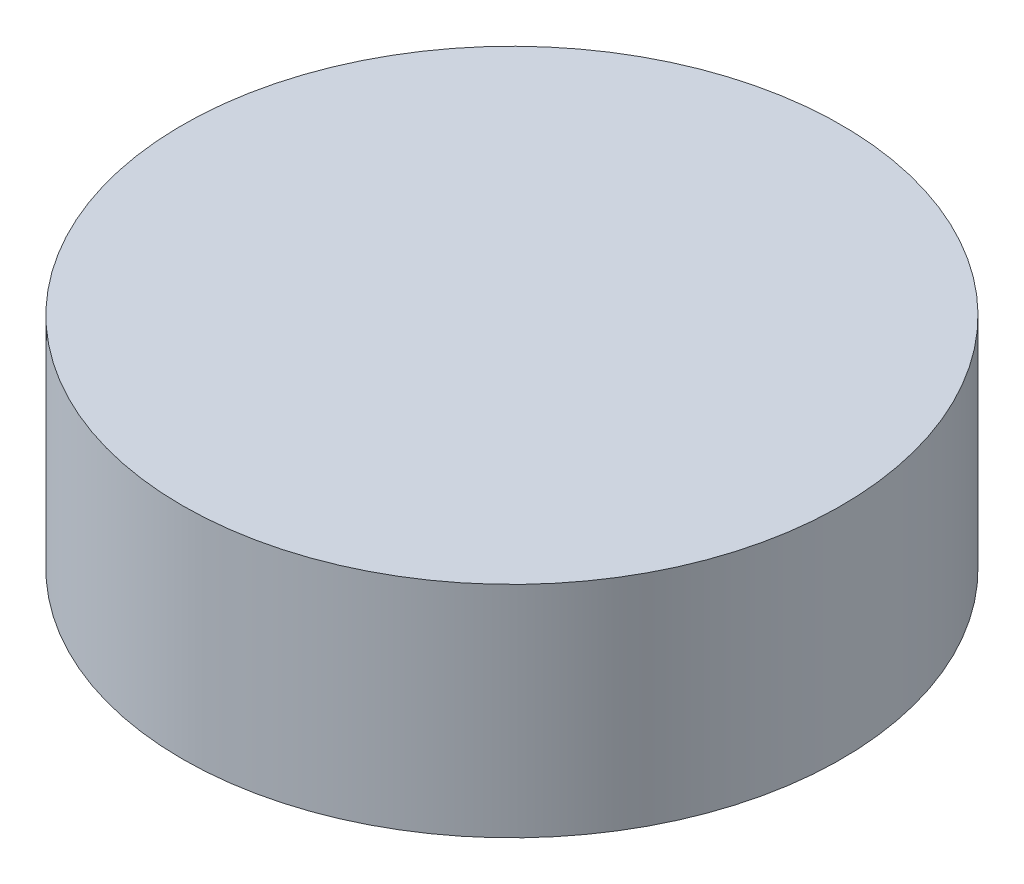
SolidWorks part; units mm, degrees
ref_plane "Front Plane" through (0, 0, 0) normal (0, 0, 1) x (1, 0, 0)
ref_plane "Top Plane" through (0, 0, 0) normal (0, 1, 0) x (1, 0, 0)
ref_plane "Right Plane" through (0, 0, 0) normal (1, 0, 0) x (0, 0, -1)
sketch "Sketch2" plane through (0, 0, 0) normal (0, 1, 0) x (1, 0, 0)
  circle A0 centre (0, 0) radius 5
  dimension "D1" = 10
extrude "Boss-Extrude1" add sketch "Sketch2" along normal blind 3.33
sketch "Sketch3" plane through (0, 3.33, 0) normal (0, 1, 0) x (1, 0, 0)
  circle A0 centre (0, 0) radius 3.335
  dimension "D1" = 6.67
sketch "Sketch5" plane through (0, 0, 0) normal (0, -1, 0) x (1, 0, 0)
  circle A0 centre (0, 0) radius 3.5
extrude "Cut-Extrude1" cut sketch "Sketch5" against normal blind 2
